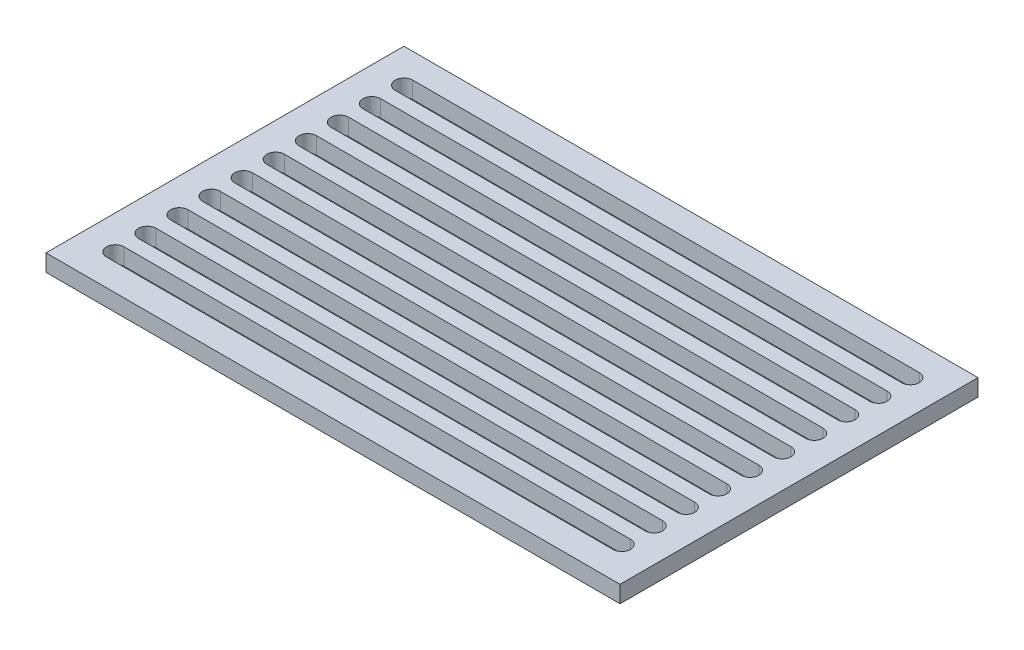
SolidWorks part; units mm, degrees
ref_plane "Front Plane" through (0, 0, 0) normal (0, 0, 1) x (1, 0, 0)
ref_plane "Top Plane" through (0, 0, 0) normal (0, 1, 0) x (1, 0, 0)
ref_plane "Right Plane" through (0, 0, 0) normal (1, 0, 0) x (0, 0, -1)
sketch "Sketch1" plane through (0, 0, 0) normal (0, 1, 0) x (1, 0, 0)
  line L0 (0, 0) -> (0, 106)
  line L1 (0, 106) -> (170, 106)
  line L2 (170, 106) -> (170, 0)
  line L3 (170, 0) -> (0, 0)
  dimension "D1" = 170
  dimension "D2" = 106
extrude "Boss-Extrude1" add sketch "Sketch1" along normal blind 5
sketch "Sketch2" plane through (0, 5, 0) normal (0, 1, 0) x (1, 0, 0)
  line L0 (0, 53) -> (170, 53) construction
  line L1 (0, 106) -> (0, 0) construction
  line L2 (170, 0) -> (170, 106) construction
  line L3 (10, 106) -> (10, 0) construction
  line L4 (170, 106) -> (0, 106) construction
  line L5 (0, 0) -> (170, 0) construction
  line L6 (0, 96) -> (170, 96) construction
  line L7 (160, 106) -> (160, 0) construction
  line L8 (10, 96) -> (45.6128, 96) construction
  line L9 (10, 96) -> (160, 96) construction
  line L10 (10, 98.6053) -> (160, 98.6053)
  line L11 (10, 93.3947) -> (160, 93.3947)
  line L12 (10, 86.5) -> (160, 86.5) construction
  line L13 (10, 89.1053) -> (160, 89.1053)
  line L14 (10, 83.8947) -> (160, 83.8947)
  line L15 (10, 77) -> (160, 77) construction
  line L16 (10, 79.6053) -> (160, 79.6053)
  line L17 (10, 74.3947) -> (160, 74.3947)
  line L18 (10, 67.5) -> (160, 67.5) construction
  line L19 (10, 70.1053) -> (160, 70.1053)
  line L20 (10, 64.8947) -> (160, 64.8947)
  line L21 (10, 58) -> (160, 58) construction
  line L22 (10, 60.6053) -> (160, 60.6053)
  line L23 (10, 55.3947) -> (160, 55.3947)
  line L24 (10, 48.5) -> (160, 48.5) construction
  line L25 (10, 51.1053) -> (160, 51.1053)
  line L26 (10, 45.8947) -> (160, 45.8947)
  line L27 (10, 39) -> (160, 39) construction
  line L28 (10, 41.6053) -> (160, 41.6053)
  line L29 (10, 36.3947) -> (160, 36.3947)
  line L30 (10, 29.5) -> (160, 29.5) construction
  line L31 (10, 32.1053) -> (160, 32.1053)
  line L32 (10, 26.8947) -> (160, 26.8947)
  line L33 (10, 20) -> (160, 20) construction
  line L34 (10, 22.6053) -> (160, 22.6053)
  line L35 (10, 17.3947) -> (160, 17.3947)
  line L36 (10, 10.5) -> (160, 10.5) construction
  line L37 (10, 13.1053) -> (160, 13.1053)
  line L38 (10, 7.8947) -> (160, 7.8947)
  arc A0 (10, 98.6053) -> (10, 93.3947) centre (10, 96) ccw
  arc A1 (160, 93.3947) -> (160, 98.6053) centre (160, 96) ccw
  arc A2 (10, 89.1053) -> (10, 83.8947) centre (10, 86.5) ccw
  arc A3 (160, 83.8947) -> (160, 89.1053) centre (160, 86.5) ccw
  arc A4 (10, 79.6053) -> (10, 74.3947) centre (10, 77) ccw
  arc A5 (160, 74.3947) -> (160, 79.6053) centre (160, 77) ccw
  arc A6 (10, 70.1053) -> (10, 64.8947) centre (10, 67.5) ccw
  arc A7 (160, 64.8947) -> (160, 70.1053) centre (160, 67.5) ccw
  arc A8 (10, 60.6053) -> (10, 55.3947) centre (10, 58) ccw
  arc A9 (160, 55.3947) -> (160, 60.6053) centre (160, 58) ccw
  arc A10 (10, 51.1053) -> (10, 45.8947) centre (10, 48.5) ccw
  arc A11 (160, 45.8947) -> (160, 51.1053) centre (160, 48.5) ccw
  arc A12 (10, 41.6053) -> (10, 36.3947) centre (10, 39) ccw
  arc A13 (160, 36.3947) -> (160, 41.6053) centre (160, 39) ccw
  arc A14 (10, 32.1053) -> (10, 26.8947) centre (10, 29.5) ccw
  arc A15 (160, 26.8947) -> (160, 32.1053) centre (160, 29.5) ccw
  arc A16 (10, 22.6053) -> (10, 17.3947) centre (10, 20) ccw
  arc A17 (160, 17.3947) -> (160, 22.6053) centre (160, 20) ccw
  arc A18 (10, 13.1053) -> (10, 7.8947) centre (10, 10.5) ccw
  arc A19 (160, 7.8947) -> (160, 13.1053) centre (160, 10.5) ccw
  point P19 (85, 96)
  point P28 (85, 86.5)
  point P35 (85, 77)
  point P42 (85, 67.5)
  point P49 (85, 58)
  point P56 (85, 48.5)
  point P63 (85, 39)
  point P70 (85, 29.5)
  point P77 (85, 20)
  point P84 (85, 10.5)
  dimension "D4" = 10
  dimension "D1" = 10
  dimension "D2" = 10
  dimension "D3" = 10
extrude "Cut-Extrude2" cut sketch "Sketch2" against normal up to next
